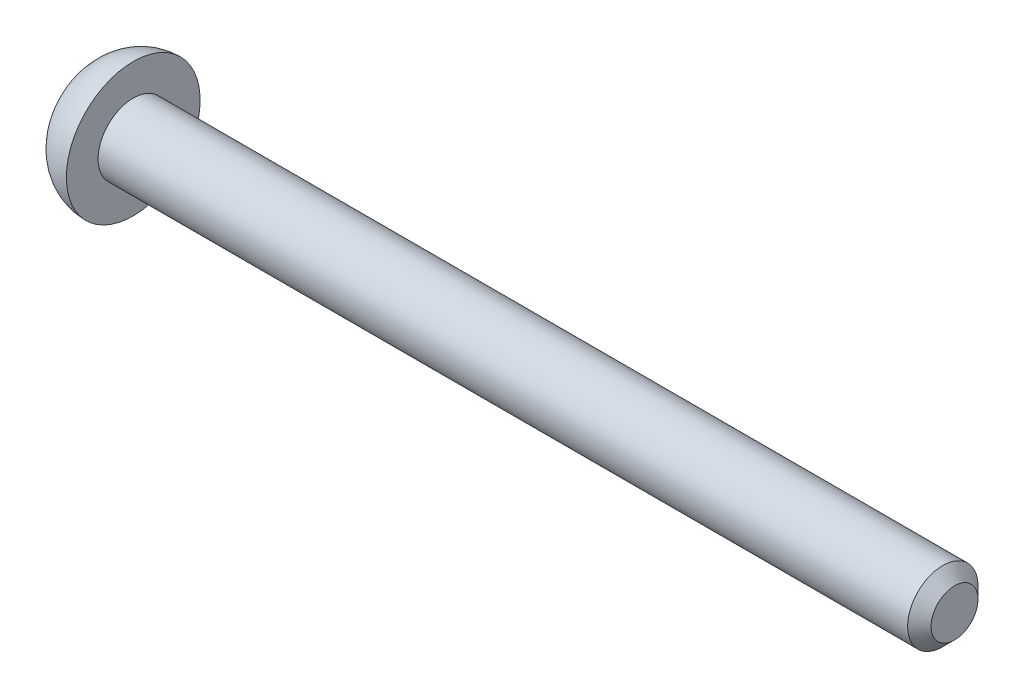
SolidWorks part; units mm, degrees
ref_plane "Front Plane" through (0, 0, 0) normal (0, 0, 1) x (1, 0, 0)
ref_plane "Top Plane" through (0, 0, 0) normal (0, 1, 0) x (1, 0, 0)
ref_plane "Right Plane" through (0, 0, 0) normal (1, 0, 0) x (0, 0, -1)
sketch "Sketch2" plane through (0, 0, 0) normal (0, 1, 0) x (1, 0, 0)
  line L0 (0, 0) -> (0, 1.5)
  line L1 (0, -3.135) -> (0, 3.135) construction
  line L2 (0, 1.5) -> (-35, 1.5)
  line L3 (-35, 1.5) -> (-35, 0) construction
  line L4 (-3.135, 0) -> (3.135, 0) construction
  line L5 (-36.65, 2.049) -> (-36.65, 0)
  line L6 (-36.65, 0) -> (0, 0)
  line L7 (-35, 2.85) -> (-35, 1.5)
  arc A0 (-36.65, 2.049) -> (-35, 2.85) centre (-35, 0.75) cw
  dimension "D2" = 35
  dimension "D3" = 2.85
  dimension "D1" = 1.65
  dimension "D4" = 1.5
revolve "Revolve1" add sketch "Sketch2" angle 360 about L6
chamfer "Chamfer1" distance 0.5 angle 45 1 edges at (0, 0, 1.5)
sketch "Sketch4" plane through (-36.65, 0, 0) normal (-1, 0, 0) x (0, 0, 1)
  line L1 (0.8389, 1.453) -> (-0.8389, 1.453) construction
  line L2 (-0.8389, 1.453) -> (-1.6778, 0) construction
  line L3 (-1.6778, 0) -> (-0.8389, -1.453) construction
  line L4 (-0.8389, -1.453) -> (0.8389, -1.453) construction
  line L5 (0.8389, -1.453) -> (1.6778, 0) construction
  line L6 (1.6778, 0) -> (0.8389, 1.453) construction
  circle A0 centre (0, 0) radius 1.453 construction
  arc A1 (-1.342, 0.0907) -> (-0.7496, 1.1169) centre (-1.7745, 1.0245) ccw
  arc A2 (-0.5924, 1.2076) -> (0.5924, 1.2076) centre (0, 2.049) ccw
  arc A3 (0.7496, 1.1169) -> (1.342, 0.0907) centre (1.7745, 1.0245) ccw
  arc A4 (1.342, -0.0907) -> (0.7496, -1.1169) centre (1.7745, -1.0245) ccw
  arc A5 (-0.5924, -1.2076) -> (0.5924, -1.2076) centre (0, -2.049) cw
  arc A6 (-0.7496, -1.1169) -> (-1.342, -0.0907) centre (-1.7745, -1.0245) ccw
  circle A7 centre (0, 0) radius 2.049 construction
  arc A8 (0.7496, 1.1169) -> (0.5924, 1.2076) centre (0.65, 1.1258) ccw
  arc A9 (1.342, -0.0907) -> (1.342, 0.0907) centre (1.3, 0) ccw
  arc A10 (0.7496, -1.1169) -> (0.5924, -1.2076) centre (0.65, -1.1258) cw
  arc A11 (-0.7496, -1.1169) -> (-0.5924, -1.2076) centre (-0.65, -1.1258) ccw
  arc A12 (-1.342, 0.0907) -> (-1.342, -0.0907) centre (-1.3, 0) ccw
  arc A13 (-0.7496, 1.1169) -> (-0.5924, 1.2076) centre (-0.65, 1.1258) cw
  circle A14 centre (0, 0) radius 2.049 construction
  point P40 (2.049, 0)
  dimension "D1" = 0.1
  dimension "D2" = 2.6
extrude "Cut-Extrude1" cut sketch "Sketch4" against normal blind 1
equation "\"d1\"= 3"
equation "\"l\"= 35"
equation "\"d2\"= 5.7"
equation "\"t\"= 1"
equation "\"k\"=1.65"
equation "\"A\"=2.8"
equation "\"D3@Sketch2\"=\"d2\" / 2"
equation "\"D1@Sketch2\"= \"k\""
equation "\"D4@Sketch2\"=\"d1\" / 2"
equation "\"D2@Sketch4\"= \"A\" - 2 * \"D1@Sketch4\""
equation "\"D1@Cut-Extrude1\"= \"t\""
equation "\"D2@Sketch2\"=\"l\""
